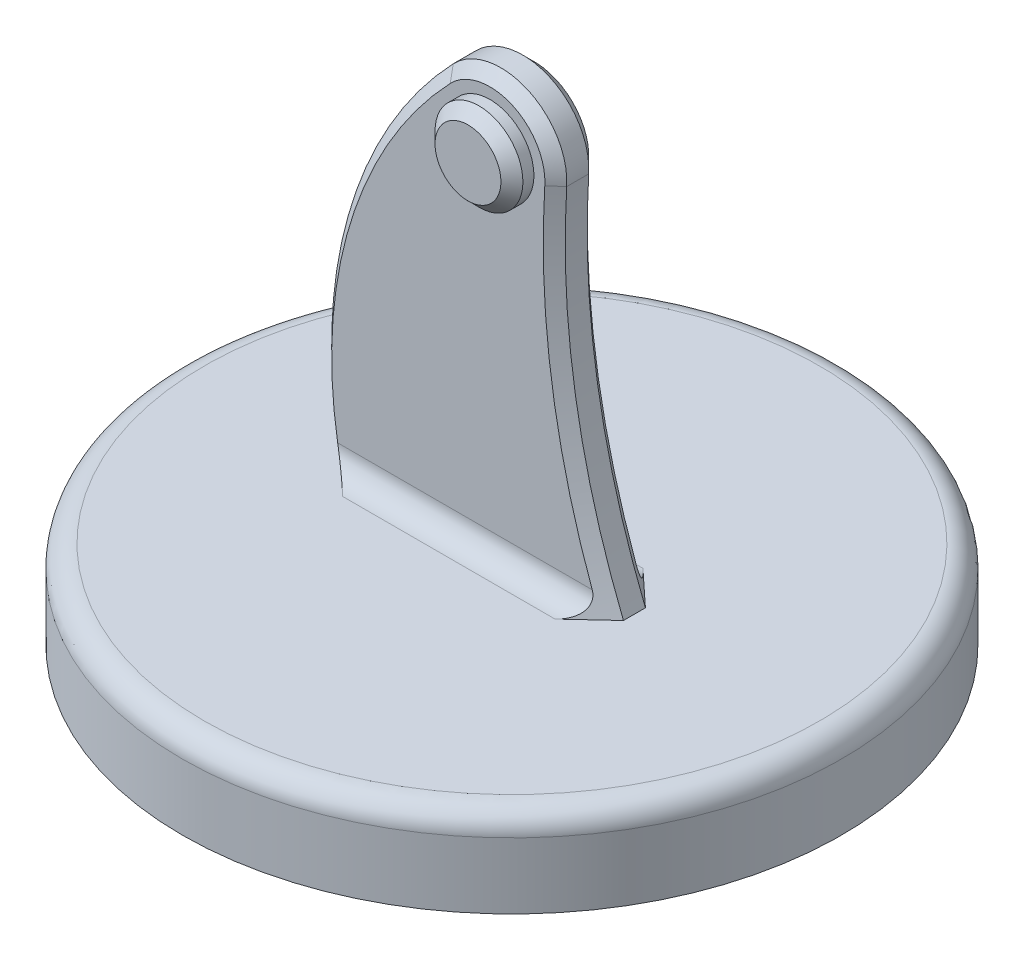
SolidWorks part; units mm, degrees
ref_plane "Ön Düzlem" through (0, 0, 0) normal (0, 0, 1) x (1, 0, 0)
ref_plane "Üst Düzlem" through (0, 0, 0) normal (0, 1, 0) x (1, 0, 0)
ref_plane "Sağ Düzlem" through (0, 0, 0) normal (1, 0, 0) x (0, 0, -1)
sketch "Çizim1" plane through (0, 0, 0) normal (0, 1, 0) x (1, 0, 0)
  circle A0 centre (0, 0) radius 75
  dimension "D1" = 150
extrude "Yükseklik-Ekstrüzyon1" add sketch "Çizim1" along normal blind 20
fillet "Radyus1" radius 5 1 edges at (0, 20, 75)
sketch "Çizim2" plane through (0, 0, 0) normal (0, 0, 1) x (1, 0, 0)
  line L0 (0, 0) -> (0, 100) construction
  line L1 (-75, 15) -> (75, 15) construction
  line L2 (-35, 15) -> (30, 15)
  arc A0 (14.9706, 99.062) -> (-10.8492, 110.3583) centre (0, 100) ccw
  arc A1 (-35, 15) -> (-10.8492, 110.3583) centre (61.4788, 41.3028) cw
  arc A2 (30, 15) -> (14.9706, 99.062) centre (194.6184, 87.8065) cw
  dimension "D2" = 30
  dimension "D5" = 180
  dimension "D6" = 100
  dimension "D1" = 100
  dimension "D3" = 35
  dimension "D4" = 30
extrude "Yükseklik-Ekstrüzyon2" add sketch "Çizim2" along normal mid plane 10 contours A0 A1 L2 A2
chamfer "Pah1" distance 2.5 angle 45 6 edges at (-34.7965, 68.3412, -5) (6.0123, 113.7423, -5) (16.9703, 58.8038, -5) (-34.7965, 68.3412, 5) (6.0123, 113.7423, 5) (16.9703, 58.8038, 5)
fillet "Radyus2" radius 5 2 edges at (-4.2415, 20, -5) (-4.2415, 20, 5)
sketch "Çizim3" plane through (0, 0, 5) normal (0, 0, 1) x (1, 0, 0)
  circle A1 centre (0, 100) radius 10
  dimension "D1" = 20
extrude "Yükseklik-Ekstrüzyon3" add sketch "Çizim3" along normal blind 5
chamfer "Pah2" distance 2.5 angle 45 1 edges at (10, 100, 10)
sketch "Çizim4" plane through (0, 0, -5) normal (0, 0, -1) x (-1, 0, 0)
  circle A0 centre (0, 100) radius 5
  dimension "D1" = 10
extrude "Kes-Ekstrüzyon1" cut sketch "Çizim4" against normal blind 10
